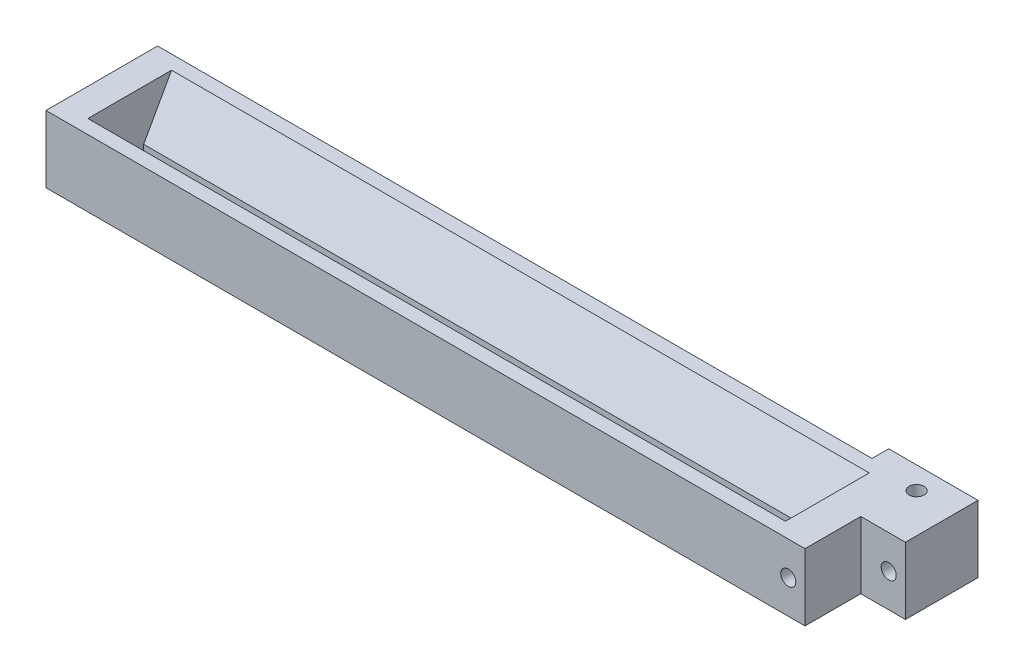
SolidWorks part; units mm, degrees
material "PLA"
ref_plane "前视基准面" through (0, 0, 0) normal (0, 0, 1) x (1, 0, 0)
ref_plane "上视基准面" through (0, 0, 0) normal (0, 1, 0) x (1, 0, 0)
ref_plane "右视基准面" through (0, 0, 0) normal (1, 0, 0) x (0, 0, -1)
sketch "草图1" plane through (0, 0, 0) normal (0, 1, 0) x (1, 0, 0)
  line L0 (-67.5, -10) -> (-67.5, 10)
  line L5 (-67.5, 10) -> (67.5, 10)
  line L6 (67.5, -10) -> (67.5, 10)
  line L7 (-62.5, -5) -> (62.5, -5) construction
  line L8 (-62.5, -5) -> (-62.5, 5) construction
  line L9 (-62.5, 5) -> (62.5, 5) construction
  line L10 (62.5, -5) -> (62.5, 5) construction
  line L11 (0, 5) -> (0, -5) construction
  line L12 (-62.5, 0) -> (62.5, 0) construction
  line L13 (-67.5, -10) -> (67.5, -10)
  point P0 (0, 0)
  point P4 (0, 0)
  dimension "D1" = 125
  dimension "D2" = 10
  dimension "D3" = 5
extrude "凸台-拉伸3" add sketch "草图1" along normal blind 12
sketch "草图2" plane through (0, 0, 0) normal (1, 0, 0) x (0, 0, -1)
  line L0 (-7.5, 12) -> (-2.5, 3)
  line L1 (-10, 12) -> (10, 12) construction
  line L2 (-3.15, 4.17) -> (3.15, 4.17) construction
  line L4 (7.5, 12) -> (-7.5, 12)
  line L6 (0, 12) -> (0, 0) construction
  line L7 (7.5, 12) -> (2.5, 3)
  line L10 (-2.5, 3) -> (-2.5, 0)
  line L11 (-10, 0) -> (10, 0) construction
  line L12 (-2.5, 0) -> (2.5, 0)
  line L13 (2.5, 0) -> (2.5, 3)
  dimension "D1" = 5
  dimension "D2" = 15
  dimension "D3" = 3
  dimension "D4" = 6.3
extrude "切除-拉伸1" cut sketch "草图2" against normal mid plane 125
ref_plane "令牌下檐面" through (0, 4.58, 0) normal (0, -1, 0) x (-1, 0, 0)
sketch "草图16" plane through (0, 12, 0) normal (0, 1, 0) x (1, 0, 0)
  line L0 (67.5, 10) -> (-67.5, 10) construction
  line L1 (60.5, 10) -> (67.5, 10)
  line L2 (60.5, 10) -> (60.5, 13)
  line L3 (60.5, 13) -> (76.5, 13)
  line L5 (67.5, -10) -> (67.5, 10) construction
  line L6 (68.5, 0) -> (76.5, 0)
  line L9 (76.5, 0) -> (76.5, 13)
  line L11 (67.5, -10) -> (68.5, -10)
  line L12 (67.5, -10) -> (67.5, 10)
  line L14 (68.5, -10) -> (68.5, 0)
  circle A0 centre (69.5, 9) radius 1.35
  dimension "D7" = 2.7
  dimension "D1" = 3
  dimension "D2" = 9
  dimension "D3" = 1
  dimension "D4" = 10
  dimension "D5" = 7
  dimension "D6" = 7
  dimension "D8" = 4
extrude "凸台-拉伸4" add sketch "草图16" against normal up to surface (12 mm away) up to face at (0, 0, 0)
sketch "草图17" plane through (0, 0, -13) normal (0, 0, -1) x (-1, 0, 0)
  line L0 (-73.5, 6) -> (-65.5, 6) construction
  line L1 (-60.5, 0) -> (-60.5, 12) construction
  line L2 (-76.5, 0) -> (-76.5, 12) construction
  line L3 (-60.5, 0) -> (-76.5, 0) construction
  circle A0 centre (-65.5, 6) radius 1.35
  circle A1 centre (-73.5, 6) radius 1.35
  dimension "D1" = 2.7
  dimension "D2" = 5
  dimension "D3" = 3
  dimension "D4" = 6
extrude "切除-拉伸12" cut sketch "草图17" against normal through all
